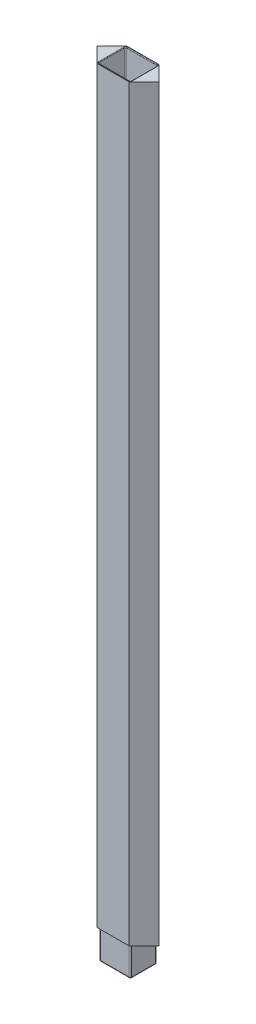
SolidWorks part; units mm, degrees
material "Plain Carbon Steel"
ref_plane "Front Plane" through (0, 0, 0) normal (0, 0, 1) x (1, 0, 0)
ref_plane "Top Plane" through (0, 0, 0) normal (0, 1, 0) x (1, 0, 0)
ref_plane "Right Plane" through (0, 0, 0) normal (1, 0, 0) x (0, 0, -1)
sketch "Sketch2" plane through (0, 0, 0) normal (0, 1, 0) x (1, 0, 0)
  line L0 (-6.604, 6.096) -> (6.604, 6.096)
  line L1 (6.604, 6.096) -> (12.7, 0)
  line L2 (12.7, 0) -> (6.604, -6.096)
  line L3 (6.604, -6.096) -> (-6.604, -6.096)
  line L4 (-6.604, -6.096) -> (-12.7, 0)
  line L5 (-12.7, 0) -> (-6.604, 6.096)
  point P9 (0, 6.096)
  dimension "D1" = 25.4
  dimension "D2" = 12.192
extrude "Boss-Extrude2" add sketch "Sketch2" along normal blind 304.8
sketch "Sketch3" plane through (0, 0, 0) normal (0, -1, 0) x (1, 0, 0)
  line L1 (-6.35, -5.334) -> (6.35, -5.334)
  line L2 (-6.35, -5.334) -> (-6.35, 5.334)
  line L3 (-6.35, 5.334) -> (6.35, 5.334)
  line L4 (6.35, -5.334) -> (6.35, 5.334)
  line L5 (-6.35, -5.334) -> (6.35, 5.334) construction
  line L6 (-6.35, 5.334) -> (6.35, -5.334) construction
  point P0 (0, 0)
  dimension "D1" = 10.668
  dimension "D2" = 12.7
extrude "Boss-Extrude3" add sketch "Sketch3" along normal blind 12.192
fillet "Fillet1" radius 0.508 12 edges at (-6.35, -12.192, 0) (-6.35, -6.096, -5.334) (-6.35, 0, 0) (6.35, -6.096, 5.334) (0, -12.192, 5.334) (-6.35, -6.096, 5.334) (0, 0, 5.334) (6.35, -12.192, 0) (0, -12.192, -5.334) (6.35, -6.096, -5.334) (6.35, 0, 0) (0, 0, -5.334)
sketch "Sketch4" plane through (0, 304.8, 0) normal (0, 1, 0) x (1, 0, 0)
  circle A0 centre (0, 0) radius 4.7625
  dimension "D1" = 9.525
extrude "Cut-Extrude1" cut sketch "Sketch4" against normal through all
sketch "Sketch5" plane through (0, 304.8, 0) normal (0, 1, 0) x (1, 0, 0)
  line L0 (6.604, 6.096) -> (-6.604, 6.096) construction
  line L1 (-6.604, -5.588) -> (6.604, -5.588)
  line L2 (-6.604, -5.588) -> (-6.604, 5.588)
  line L3 (-6.604, 5.588) -> (6.604, 5.588)
  line L4 (6.604, -5.588) -> (6.604, 5.588)
  line L5 (-6.604, -5.588) -> (6.604, 5.588) construction
  line L6 (-6.604, 5.588) -> (6.604, -5.588) construction
  point P0 (0, 0)
  dimension "D1" = 0.508
  dimension "D2" = 13.208
  dimension "D3" = 11.176
extrude "Cut-Extrude2" cut sketch "Sketch5" against normal blind 12.7
fillet "Fillet3" radius 0.381 8 edges at (6.604, 298.45, -5.588) (6.604, 292.1, 0) (6.604, 298.45, 5.588) (-6.604, 298.45, 5.588) (0, 292.1, 5.588) (-6.604, 292.1, 0) (-6.604, 298.45, -5.588) (0, 292.1, -5.588)
fillet "Fillet4" radius 0.254 8 edges at (6.4924, 304.8, 5.4764) (0, 304.8, 5.588) (-6.4924, 304.8, 5.4764) (-6.604, 304.8, 0) (-6.4924, 304.8, -5.4764) (0, 304.8, -5.588) (6.4924, 304.8, -5.4764) (6.604, 304.8, 0)
